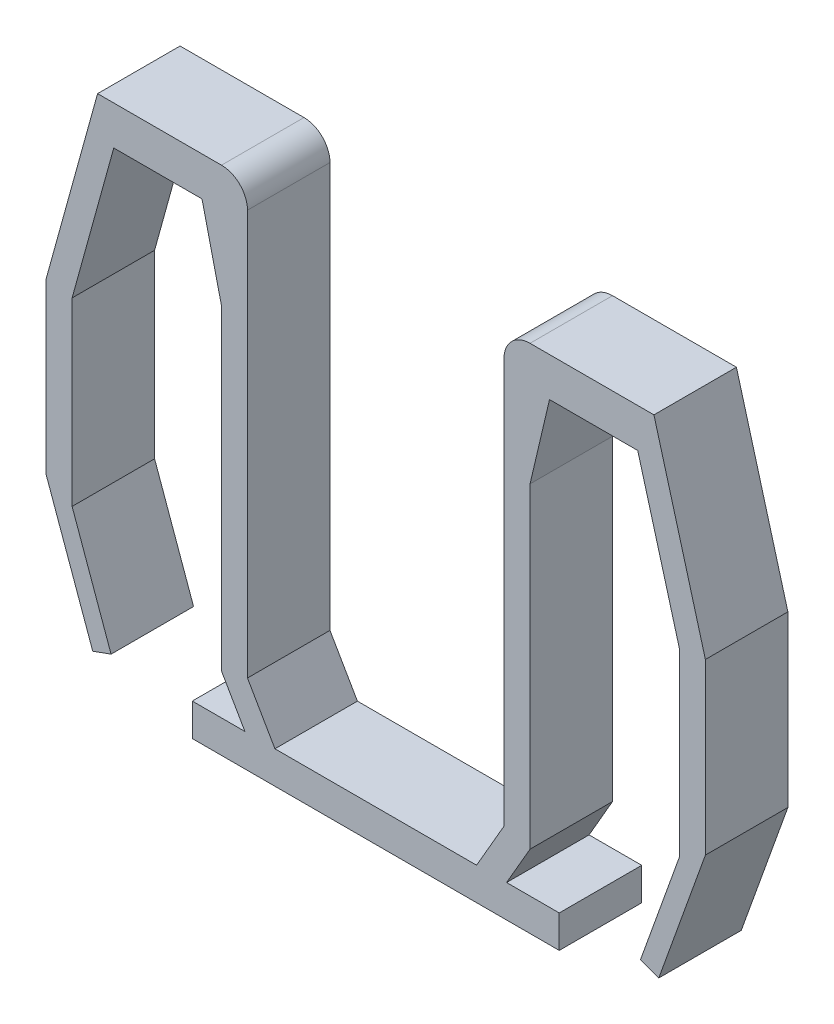
SolidWorks part; units mm, degrees
material "PE High Density"
ref_plane "Front Plane" through (0, 0, 0) normal (0, 0, 1) x (1, 0, 0)
ref_plane "Top Plane" through (0, 0, 0) normal (0, 1, 0) x (1, 0, 0)
ref_plane "Right Plane" through (0, 0, 0) normal (1, 0, 0) x (0, 0, -1)
sketch "Sketch1" plane through (0, 0, 0) normal (0, 0, 1) x (1, 0, 0)
  line L0 (7, -61.2) -> (-5, -27.8)
  line L1 (-5, -27.8) -> (-5, 27.8)
  line L2 (-5, 27.8) -> (7.8295, 74.2)
  line L3 (7.8295, 74.2) -> (35, 74.2)
  line L4 (35, 74.2) -> (41, 48.7)
  line L5 (35, 50.63) -> (35, 70.2) construction
  line L6 (41, 48.7) -> (41, -48.7)
  line L7 (-4.7644, -28.4557) -> (7, -61.2) construction
  line L8 (31, 74.2) -> (10.8736, 74.2) construction
  line L9 (32, -61.2) -> (32, -71.2)
  line L10 (32, -71.2) -> (145, -71.2)
  line L11 (7.0182, 71.266) -> (-4.8553, 28.3232) construction
  line L12 (-5, 27.2572) -> (-5, -27.1032) construction
  line L13 (7, -61.2) -> (1.3534, -63.2287)
  line L14 (1.3534, -63.2287) -> (-13, -23.2785)
  line L15 (-13, -23.2785) -> (-13, 28.8856)
  line L16 (-13, 28.8856) -> (2.8473, 86.2)
  line L17 (2.8473, 86.2) -> (49, 86.2)
  line L18 (49, 86.2) -> (49, -46.5564)
  line L19 (57.4545, -61.2) -> (119.5455, -61.2)
  line L20 (49, -46.5564) -> (57.4545, -61.2)
  line L21 (32, -61.2) -> (48.2169, -61.2)
  line L22 (88.5, -61.2) -> (88.5, -46.5564) construction
  line L23 (170, -61.2) -> (175.6466, -63.2287)
  line L24 (175.6466, -63.2287) -> (190, -23.2785)
  line L25 (170, -61.2) -> (182, -27.8)
  line L26 (190, -23.2785) -> (190, 28.8856)
  line L27 (182, -27.8) -> (182, 27.8)
  line L28 (190, 28.8856) -> (174.1527, 86.2)
  line L29 (182, 27.8) -> (169.1705, 74.2)
  line L30 (169.1705, 74.2) -> (142, 74.2)
  line L31 (174.1527, 86.2) -> (128, 86.2)
  line L32 (142, 74.2) -> (136, 48.7)
  line L33 (128, 86.2) -> (128, -46.5564)
  line L34 (128, -46.5564) -> (119.5455, -61.2)
  line L35 (145, -61.2) -> (128.7831, -61.2)
  line L36 (145, -61.2) -> (145, -71.2)
  line L37 (41, -48.7) -> (48.2169, -61.2)
  line L38 (136, 48.7) -> (136, -48.7)
  line L39 (136, -48.7) -> (128.7831, -61.2)
  line L40 (41, -48.7) -> (41, 48.7) construction
  point P6 (141, -48.7)
  point P20 (41, -48.7)
  point P26 (50.5523, -61.2)
  point P30 (49, -44.5142)
  point P32 (41, -48.7)
  point P51 (88.5, -61.2)
  point P57 (60.2212, -61.2)
  point P58 (91, -40.5881)
  dimension "D1" = 6
  dimension "D7" = 8
  dimension "D2" = 8
  dimension "D3" = 8
  dimension "D4" = 12
  dimension "D5" = 8
  dimension "D6" = 10
  dimension "D8" = 60
extrude "Boss-Extrude1" add sketch "Sketch1" against normal blind 25.4
fillet "Fillet1" radius 8 2 edges at (49, 86.2, -12.7) (128, 86.2, -12.7)
